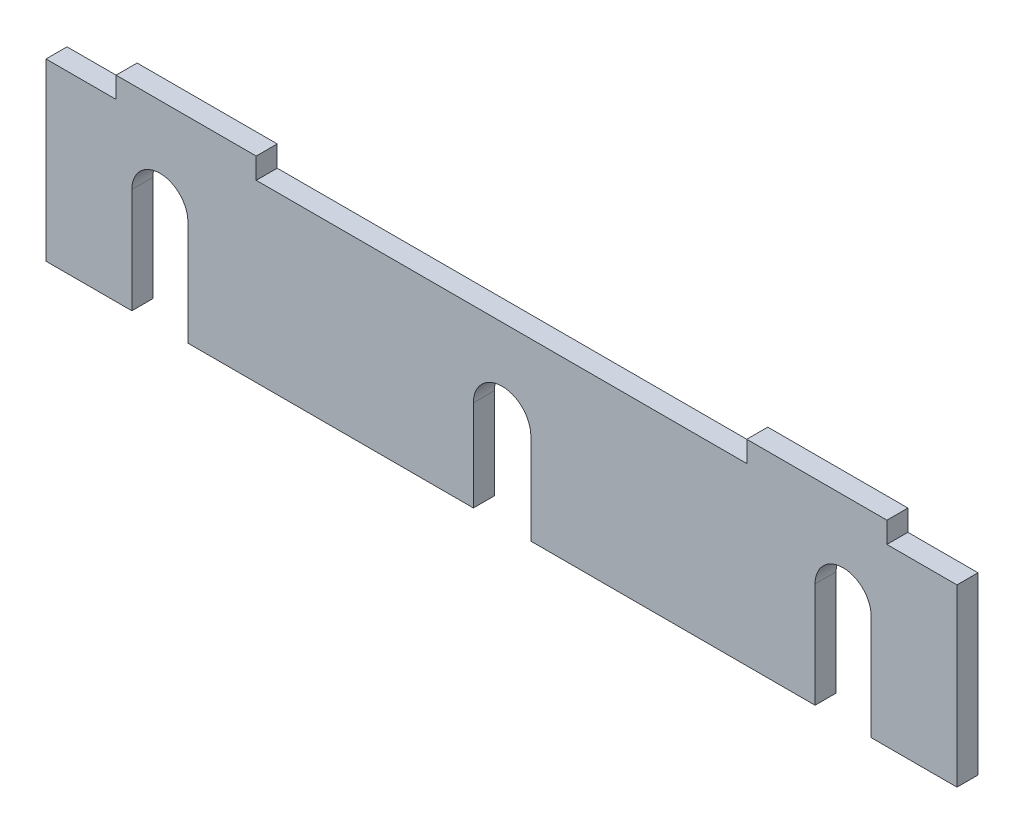
SolidWorks part; units mm, degrees
ref_plane "Front Plane" through (0, 0, 0) normal (0, 0, 1) x (1, 0, 0)
ref_plane "Top Plane" through (0, 0, 0) normal (0, 1, 0) x (1, 0, 0)
ref_plane "Right Plane" through (0, 0, 0) normal (1, 0, 0) x (0, 0, -1)
sketch "Sketch1" plane through (0, 0, 0) normal (0, 0, 1) x (1, 0, 0)
  line L0 (0, 0) -> (10, 0)
  line L1 (0, 0) -> (0, -25)
  line L2 (0, -25) -> (12.25, -25)
  line L3 (12.25, -25) -> (12.25, -10)
  line L4 (20.25, -10) -> (20.25, -25)
  line L5 (20.25, -25) -> (60.99, -25)
  line L6 (60.99, -25) -> (60.99, -12)
  line L7 (130, 0) -> (130, -25)
  line L8 (130, -25) -> (117.75, -25)
  line L9 (117.75, -25) -> (117.75, -10)
  line L10 (109.75, -10) -> (109.75, -25)
  line L11 (109.75, -25) -> (69.19, -25)
  line L12 (69.19, -25) -> (69.19, -12)
  line L13 (10, 0) -> (10, 3)
  line L14 (10, 3) -> (30, 3)
  line L15 (30, 3) -> (30, 0)
  line L16 (100, 0) -> (100, 3)
  line L17 (100, 3) -> (120, 3)
  line L18 (120, 3) -> (120, 0)
  line L19 (30, 0) -> (100, 0)
  line L20 (120, 0) -> (130, 0)
  arc A0 (20.25, -10) -> (12.25, -10) centre (16.25, -10) ccw
  arc A1 (69.19, -12) -> (60.99, -12) centre (65.09, -12) ccw
  arc A2 (117.75, -10) -> (109.75, -10) centre (113.75, -10) ccw
  dimension "D3" = 8
  dimension "D4" = 48.84
  dimension "D13" = 4.1
  dimension "D14" = 4
  dimension "D1" = 130
  dimension "D2" = 97.5
  dimension "D5" = 10
  dimension "D6" = 3
  dimension "D7" = 20
  dimension "D8" = 10
  dimension "D9" = 25
  dimension "D10" = 10
  dimension "D11" = 12
  dimension "D12" = 10
extrude "Boss-Extrude1" add sketch "Sketch1" along normal blind 3 contours L15 L19 L16 L17 L18 L20 L7 L8 L9 A2 L10 L11 L12 A1 L6 L5 L4 A0 L3 L2 L1 L0 L13 L14
